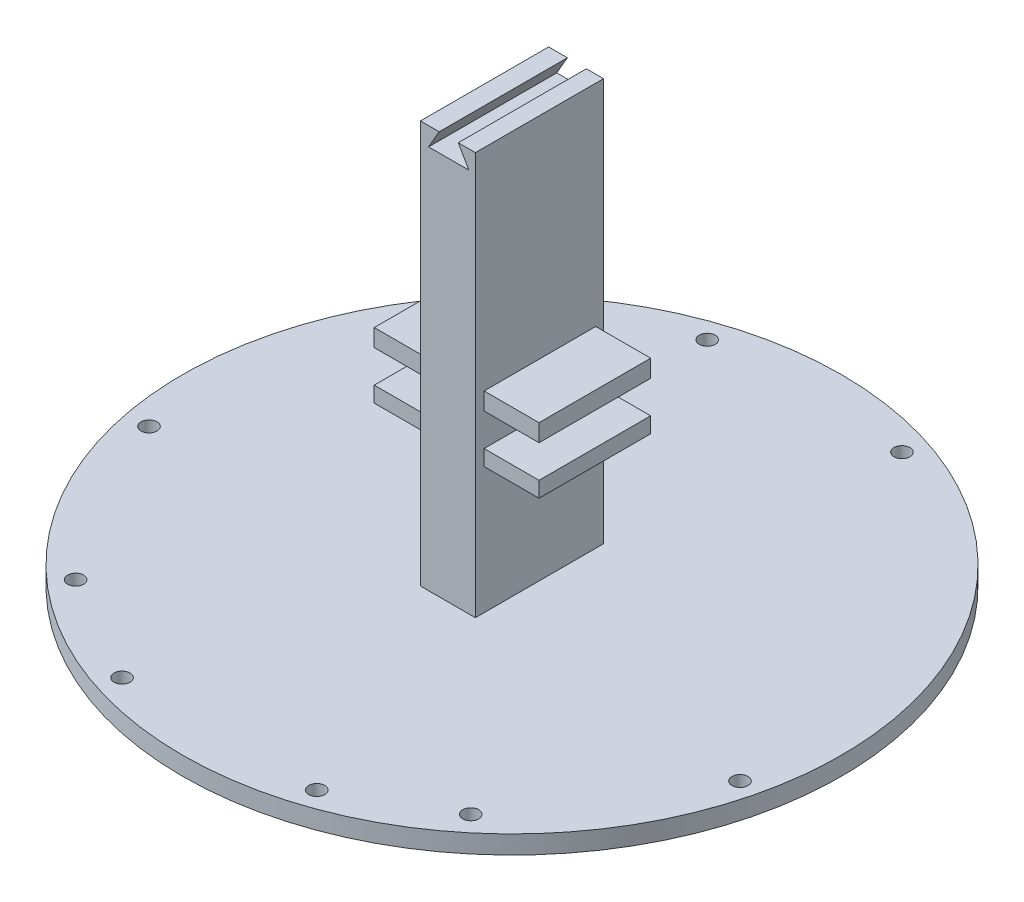
SolidWorks part; units mm, degrees
ref_plane "Front Plane" through (0, 0, 0) normal (0, 0, 1) x (1, 0, 0)
ref_plane "Top Plane" through (0, 0, 0) normal (0, 1, 0) x (1, 0, 0)
ref_plane "Right Plane" through (0, 0, 0) normal (1, 0, 0) x (0, 0, -1)
sketch "Sketch1" plane through (0, 0, 0) normal (0, 1, 0) x (1, 0, 0)
  circle A0 centre (0, 0) radius 90
  dimension "D1" = 180
extrude "Boss-Extrude1" add sketch "Sketch1" along normal blind 5
sketch "Sketch2" plane through (0, 5, 0) normal (0, 1, 0) x (1, 0, 0)
  line L1 (7.5, -17.5) -> (-7.5, -17.5)
  line L2 (7.5, -17.5) -> (7.5, 17.5)
  line L3 (7.5, 17.5) -> (-7.5, 17.5)
  line L4 (-7.5, -17.5) -> (-7.5, 17.5)
  line L5 (7.5, -17.5) -> (-7.5, 17.5) construction
  line L6 (7.5, 17.5) -> (-7.5, -17.5) construction
  point P0 (0, 0)
  dimension "D1" = 35
  dimension "D2" = 15
extrude "Boss-Extrude2" add sketch "Sketch2" along normal blind 110
sketch "Sketch3" plane through (0, 0, 17.5) normal (0, 0, 1) x (1, 0, 0)
  line L0 (-2.3736, 115) -> (2.8264, 115)
  line L1 (-7.5, 115) -> (7.5, 115) construction
  line L2 (5.7264, 109.9771) -> (-5.2736, 109.9771)
  line L3 (-5.2736, 109.9771) -> (-2.3736, 115)
  line L4 (2.8264, 115) -> (5.7264, 109.9771)
  point P5 (0.2264, 115)
  point P8 (0.2264, 109.9771)
  dimension "D1" = 5.2
  dimension "D2" = 11
  dimension "D3" = 60
  dimension "D4" = 5.8
extrude "Cut-Extrude1" cut sketch "Sketch3" against normal blind 36
sketch "Sketch4" plane through (0, 0, 0) normal (0, -1, 0) x (-1, 0, 0)
  line L0 (-82.2453, -19.9781) -> (-53.3466, -64.6125)
  line L1 (56.0932, -63.0822) -> (82.3103, -16.8252)
  line L2 (26.585, -79.9073) -> (-26.585, -79.9073)
  line L3 (26.585, 79.9073) -> (-26.585, 79.9073)
  circle A0 centre (0, 0) radius 79.9073
  arc A1 (-79.9073, 0) -> (-67.7959, -42.2953) centre (0, 0) ccw
  arc A2 (79.9073, 0) -> (69.2018, -39.9537) centre (0, 0) cw
  circle A3 centre (-82.2453, -19.9781) radius 2.1826
  circle A4 centre (-53.3466, -64.6125) radius 2.1826
  circle A5 centre (82.3103, -16.8252) radius 2.1826
  circle A6 centre (56.0932, -63.0822) radius 2.1826
  circle A7 centre (-26.585, -79.9073) radius 2.1826
  circle A8 centre (26.585, -79.9073) radius 2.1826
  circle A9 centre (-26.585, 79.9073) radius 2.1826
  circle A10 centre (26.585, 79.9073) radius 2.1826
  point P10 (-67.7959, -42.2953)
  point P15 (69.2018, -39.9537)
  point P20 (0, -79.9073)
  point P25 (0, 79.9073)
  dimension "D1" = 53.173
  dimension "D2" = 4.3651
  dimension "D3" = 4.3651
  dimension "D5" = 4.3651
  dimension "D6" = 4.3651
  dimension "D7" = 53.17
  dimension "D8" = 4.3651
  dimension "D9" = 4.3651
  dimension "D10" = 4.3651
  dimension "D11" = 4.3651
  dimension "D4" = 53.17
  dimension "D12" = 53.17
extrude "Cut-Extrude2" cut sketch "Sketch4" against normal blind 62
sketch "Sketch6" plane through (7.5, 0, 0) normal (1, 0, 0) x (0, 0, -1)
  line L0 (-15.121, 57.445) -> (15.3709, 57.445)
  line L1 (15.3709, 57.445) -> (15.3709, 39.5747)
  line L2 (15.3709, 39.5747) -> (-15.121, 39.5747)
  line L3 (-15.121, 39.5747) -> (-15.121, 57.445)
  line L4 (-15.121, 43.8236) -> (15.3709, 43.8236)
  line L5 (15.3709, 43.8236) -> (15.3709, 52.6962)
  line L6 (15.3709, 52.6962) -> (-15.121, 52.6962)
extrude "Boss-Extrude4" add sketch "Sketch6" along normal blind 15 and the other way blind 30 contours L6 L1 L0 L3 | L4 L3 L2 L1
